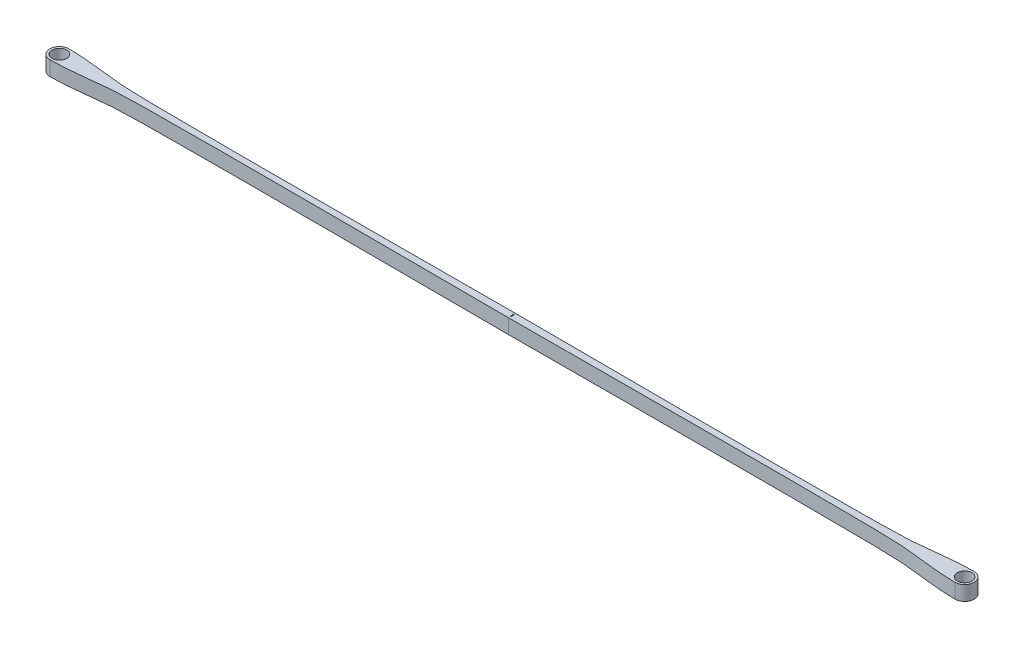
SolidWorks part; units mm, degrees
ref_plane "Front Plane" through (0, 0, 0) normal (0, 0, 1) x (1, 0, 0)
ref_plane "Top Plane" through (0, 0, 0) normal (0, 1, 0) x (1, 0, 0)
ref_plane "Right Plane" through (0, 0, 0) normal (1, 0, 0) x (0, 0, -1)
sketch "Sketch2" plane through (0, 0, 0) normal (0, 1, 0) x (1, 0, 0)
  line L1 (-1.1, 0) -> (1.1, 0) construction
  line L2 (61.9, 0.5) -> (61.9, -0.5)
  circle A0 centre (0, 0) radius 1.3
  spline S0 degree 3 poles (0, 1.3) (2.1583, 1.3) (7.6059, 0.5483) (11.0616, 0.324) (61.9, 0.5) knots 0 0 0 0 0.427834 1 1 1 1
  spline S1 degree 3 poles (0, -1.3) (2.1583, -1.3) (7.6059, -0.5483) (11.0616, -0.324) (61.9, -0.5) knots 0 0 0 0 0.427834 1 1 1 1
  dimension "D1" = 61.9
  dimension "D5" = 2.6
  dimension "D4" = 7.1253
  dimension "D6" = 15.0773
  dimension "D2" = 7.1943
  dimension "D3" = 1.364
  dimension "D7" = 1
extrude "Boss-Extrude1" add sketch "Sketch2" along normal blind 2 contours A0 S1 L2 S0
sketch "Sketch3" plane through (0, 2, 0) normal (0, 1, 0) x (1, 0, 0)
  circle A0 centre (0, 0) radius 1
  dimension "D1" = 2
extrude "Cut-Extrude1" cut sketch "Sketch3" against normal through all
ref_plane "Plane1" through (61.9, 0, 0) normal (1, 0, 0) x (0, 0, -1)
mirror "Mirror1" about plane through (61.9, 0, 0) normal (1, 0, 0) of "Boss-Extrude1", "Cut-Extrude1"
sketch "Sketch4" plane through (0, 2, 0) normal (0, 1, 0) x (1, 0, 0)
  line L0 (61.85, -0.2) -> (61.95, 0.3) construction
  line L1 (61.85, -0.2) -> (61.95, -0.2)
  line L2 (61.85, -0.2) -> (61.85, 0.3)
  line L3 (61.85, 0.3) -> (61.95, 0.3)
  line L4 (61.95, -0.2) -> (61.95, 0.3)
  line L5 (61.9, -1.1) -> (61.9, 1.1) construction
  point P4 (61.9, 0.05)
  point P7 (0, 0)
  dimension "D1" = 0.5
  dimension "D2" = 0.1
  dimension "D3" = 1.1
extrude "Cut-Extrude2" cut sketch "Sketch4" against normal blind 0.5
